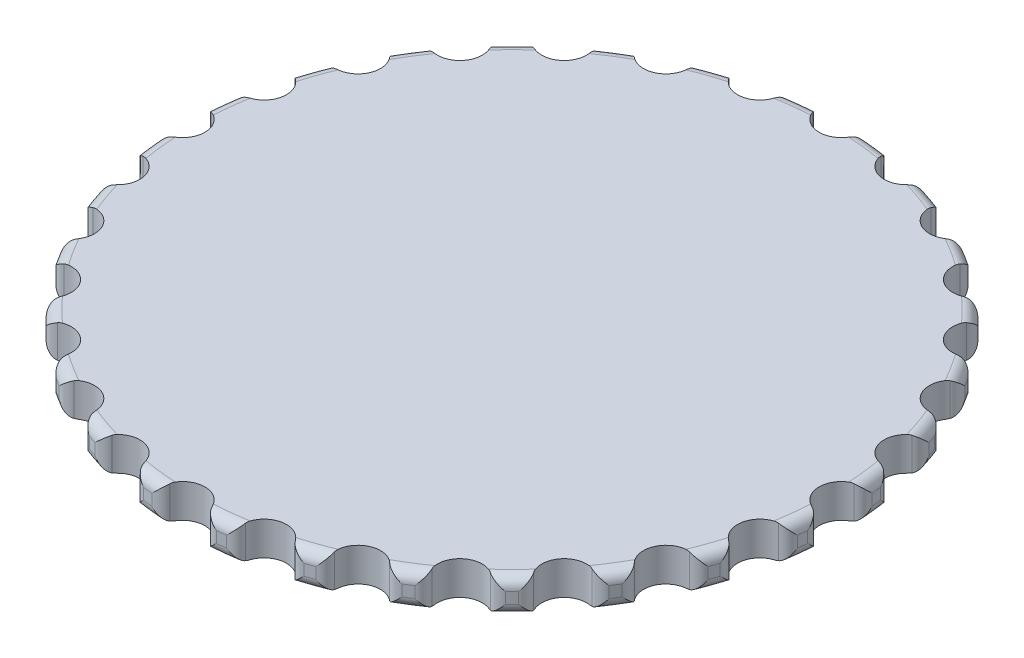
SolidWorks part; units mm, degrees
ref_plane "Front Plane" through (0, 0, 0) normal (0, 0, 1) x (1, 0, 0)
ref_plane "Top Plane" through (0, 0, 0) normal (0, 1, 0) x (1, 0, 0)
ref_plane "Right Plane" through (0, 0, 0) normal (1, 0, 0) x (0, 0, -1)
sketch "Sketch2" plane through (0, 0, 0) normal (0, 1, 0) x (1, 0, 0)
  circle A0 centre (0, 0) radius 29.4
  point P3 (-44.4574, 14.9437)
  dimension "D1" = 58.8
extrude "Boss-Extrude1" add sketch "Sketch2" along normal blind 3
sketch "Sketch3" plane through (0, 3, 0) normal (0, 1, 0) x (1, 0, 0)
  circle A0 centre (0, 29.4) radius 2
  circle A1 centre (0, 0) radius 29.4 construction
  dimension "D1" = 4
extrude "Cut-Extrude1" cut sketch "Sketch3" against normal blind 3
pattern_circular "CirPattern1" count 28 over 360 about axis through (0, 0, 0) along (0, 1, 0) of "Cut-Extrude1"
fillet "Fillet1" radius 1 112 edges at (29.332, 1.5, -1.9988) (29.332, 1.5, 1.9988) (29.2151, 0, 3.2918) (27.7502, 0, 9.7102) (29.0413, 1.5, 4.5783) (28.1518, 1.5, 8.4757) (27.7502, 3, 9.7102) (29.2151, 3, 3.2918) (24.8937, 0, 15.6417) (27.2945, 1.5, 10.9258) (25.5599, 1.5, 14.5276) (24.8937, 3, 15.6417) (20.7889, 0, 20.7889) (24.1789, 1.5, 16.7254) (21.6864, 1.5, 19.8509) (20.7889, 3, 20.7889) (15.6417, 0, 24.8937) (19.8509, 1.5, 21.6864) (16.7254, 1.5, 24.1789) (15.6417, 3, 24.8937) (9.7102, 0, 27.7502) (14.5276, 1.5, 25.5599) (10.9258, 1.5, 27.2945) (9.7102, 3, 27.7502) (3.2918, 0, 29.2151) (8.4757, 1.5, 28.1518) (4.5783, 1.5, 29.0413) (3.2918, 3, 29.2151) (-3.2918, 0, 29.2151) (1.9988, 1.5, 29.332) (-1.9988, 1.5, 29.332) (-3.2918, 3, 29.2151) (-9.7102, 0, 27.7502) (-4.5783, 1.5, 29.0413) (-8.4757, 1.5, 28.1518) (-9.7102, 3, 27.7502) (-15.6417, 0, 24.8937) (-10.9258, 1.5, 27.2945) (-14.5276, 1.5, 25.5599) (-15.6417, 3, 24.8937) (-20.7889, 0, 20.7889) (-16.7254, 1.5, 24.1789) (-19.8509, 1.5, 21.6864) (-20.7889, 3, 20.7889) (-24.8937, 0, 15.6417) (-21.6864, 1.5, 19.8509) (-24.1789, 1.5, 16.7254) (-24.8937, 3, 15.6417) (-27.7502, 0, 9.7102) (-25.5599, 1.5, 14.5276) (-27.2945, 1.5, 10.9258) (-27.7502, 3, 9.7102) (-29.2151, 0, 3.2918) (-28.1518, 1.5, 8.4757) (-29.0413, 1.5, 4.5783) (-29.2151, 3, 3.2918) (-29.2151, 0, -3.2918) (-29.332, 1.5, 1.9988) (-29.332, 1.5, -1.9988) (-29.2151, 3, -3.2918) (-27.7502, 0, -9.7102) (-29.0413, 1.5, -4.5783) (-28.1518, 1.5, -8.4757) (-27.7502, 3, -9.7102) (-24.8937, 0, -15.6417) (-27.2945, 1.5, -10.9258) (-25.5599, 1.5, -14.5276) (-24.8937, 3, -15.6417) (-20.7889, 0, -20.7889) (-24.1789, 1.5, -16.7254) (-21.6864, 1.5, -19.8509) (-20.7889, 3, -20.7889) (-15.6417, 0, -24.8937) (-19.8509, 1.5, -21.6864) (-16.7254, 1.5, -24.1789) (-15.6417, 3, -24.8937) (-9.7102, 0, -27.7502) (-14.5276, 1.5, -25.5599) (-10.9258, 1.5, -27.2945) (-9.7102, 3, -27.7502) (-8.4757, 1.5, -28.1518) (-4.5783, 1.5, -29.0413) (-3.2918, 3, -29.2151) (-3.2918, 0, -29.2151) (-1.9988, 1.5, -29.332) (1.9988, 1.5, -29.332) (3.2918, 0, -29.2151) (9.7102, 0, -27.7502) (4.5783, 1.5, -29.0413) (8.4757, 1.5, -28.1518) (9.7102, 3, -27.7502) (3.2918, 3, -29.2151) (15.6417, 0, -24.8937) (10.9258, 1.5, -27.2945) (14.5276, 1.5, -25.5599) (15.6417, 3, -24.8937) (20.7889, 0, -20.7889) (16.7254, 1.5, -24.1789) (19.8509, 1.5, -21.6864) (20.7889, 3, -20.7889) (24.8937, 0, -15.6417) (21.6864, 1.5, -19.8509) (24.1789, 1.5, -16.7254) (24.8937, 3, -15.6417) (27.7502, 0, -9.7102) (25.5599, 1.5, -14.5276) (27.2945, 1.5, -10.9258) (27.7502, 3, -9.7102) (29.2151, 0, -3.2918) (28.1518, 1.5, -8.4757) (29.0413, 1.5, -4.5783) (29.2151, 3, -3.2918)
sketch "Sketch4" plane through (0, 3, 0) normal (0, 1, 0) x (1, 0, 0)
  circle A0 centre (0, 0) radius 4
  dimension "D1" = 8
